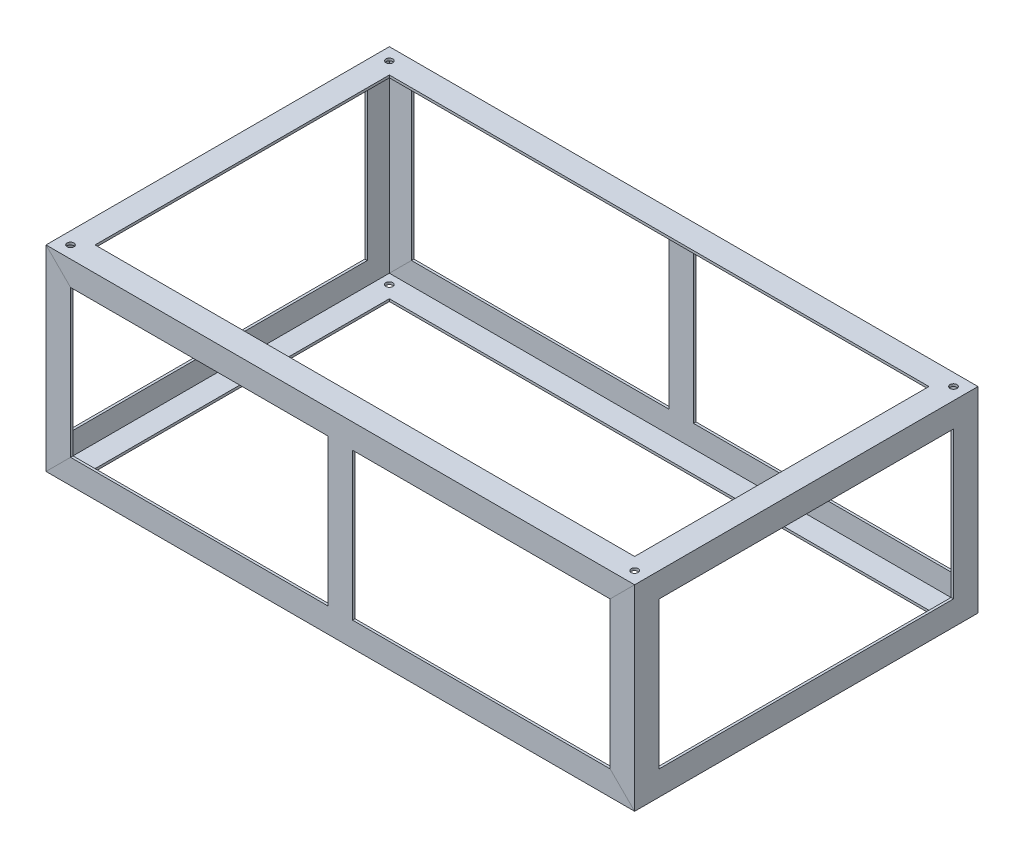
SolidWorks part; units mm, degrees
ref_plane "Front Plane" through (0, 0, 0) normal (0, 0, 1) x (1, 0, 0)
ref_plane "Top Plane" through (0, 0, 0) normal (0, 1, 0) x (1, 0, 0)
ref_plane "Right Plane" through (0, 0, 0) normal (1, 0, 0) x (0, 0, -1)
sketch "Sketch1" plane through (0, 0, 0) normal (1, 0, 0) x (0, 0, -1)
  line L0 (0, 0) -> (0, -50)
  line L1 (0, 0) -> (50, 0)
  line L2 (5, -5) -> (5, -50)
  line L3 (5, -5) -> (50, -5)
  line L4 (0, -50) -> (5, -50)
  line L5 (50, -5) -> (50, 0)
  dimension "D1" = 5
sketch "Sketch3" plane through (0, 0, 0) normal (0, 0, 1) x (1, 0, 0)
  line L1 (0, 0) -> (1200, 0)
  line L2 (0, 0) -> (0, -400)
  line L3 (0, -400) -> (1200, -400)
  line L4 (1200, 0) -> (1200, -400)
sweep "Sweep1" add profiles "Sketch1" path "Sketch3"
ref_plane "Plane2" through (0, 0, -350) normal (0, 0, 1) x (1, 0, 0)
sketch "Sketch8" plane through (0, 0, 0) normal (0, 0, 1) x (1, 0, 0)
  line L0 (600, -50) -> (600, 49950) construction
  line L1 (1150, -50) -> (50, -50) construction
  line L2 (1150, -350) -> (50, -350) construction
  line L4 (575, -50) -> (625, -50)
  line L5 (575, -50) -> (575, -350)
  line L6 (575, -350) -> (625, -350)
  line L7 (625, -50) -> (625, -350)
  point P4 (600, -50)
extrude "Boss-Extrude2" add sketch "Sketch8" against normal blind 5
mirror "Mirror8" about plane through (0, 0, -350) normal (0, 0, 1) of bodies 105
sketch "Sketch10" plane through (0, 0, -650) normal (0, 0, 1) x (1, 0, 0)
  line L0 (0, 0) -> (50, 0)
  line L1 (1200, 0) -> (0, 0) construction
  line L2 (0, 0) -> (0, -50)
  line L3 (0, -400) -> (0, 0) construction
  line L4 (5, -5) -> (5, -50)
  line L5 (5, -5) -> (50, -5)
  line L6 (50, -5) -> (50, 0)
  line L7 (0, -50) -> (5, -50)
  line L8 (5, -50) -> (5.1526, -50.1969)
  line L9 (600, 0) -> (600, 191.0961) construction
  line L10 (50, -200) -> (-49950, -200) construction
  line L11 (50, -350) -> (50, -50) construction
  line L12 (1195, -50) -> (1194.8474, -50.1969)
  line L13 (1200, -50) -> (1195, -50)
  line L14 (1150, -5) -> (1150, 0)
  line L15 (1195, -5) -> (1150, -5)
  line L16 (1195, -5) -> (1195, -50)
  line L17 (1200, 0) -> (1200, -50)
  line L18 (1200, 0) -> (1150, 0)
  line L19 (1200, -400) -> (1150, -400)
  line L20 (1200, -400) -> (1200, -350)
  line L21 (1195, -395) -> (1195, -350)
  line L22 (1195, -395) -> (1150, -395)
  line L23 (1150, -395) -> (1150, -400)
  line L24 (1200, -350) -> (1195, -350)
  line L25 (1195, -350) -> (1194.8474, -349.8031)
  line L26 (5, -350) -> (5.1526, -349.8031)
  line L27 (0, -350) -> (5, -350)
  line L28 (50, -395) -> (50, -400)
  line L29 (5, -395) -> (50, -395)
  line L30 (5, -395) -> (5, -350)
  line L31 (0, -400) -> (0, -350)
  line L32 (0, -400) -> (50, -400)
  point P18 (50, -200)
  dimension "D1" = 5
extrude "Boss-Extrude3" add sketch "Sketch10" along normal up to surface (600 mm away) up to face at (600, -397.5, -50)
sketch "Sketch11" plane through (0, -400, 0) normal (0, -1, 0) x (1, 0, 0)
  line L0 (600, -700) -> (600, 0) construction
  line L1 (1200, -700) -> (0, -700) construction
  line L2 (1200, 0) -> (0, 0) construction
  line L3 (0, -350) -> (1200, -350) construction
  line L4 (0, -700) -> (0, 0) construction
  line L5 (1200, 0) -> (1200, -700) construction
  circle A0 centre (25, -25) radius 7
  circle A1 centre (1175, -25) radius 7
  circle A2 centre (1175, -675) radius 7
  circle A3 centre (25, -675) radius 7
extrude "Cut-Extrude1" cut sketch "Sketch11" against normal blind 405
ref_plane "Plane3" through (600, 0, 0) normal (-1, 0, 0) x (0, 0, 1)
